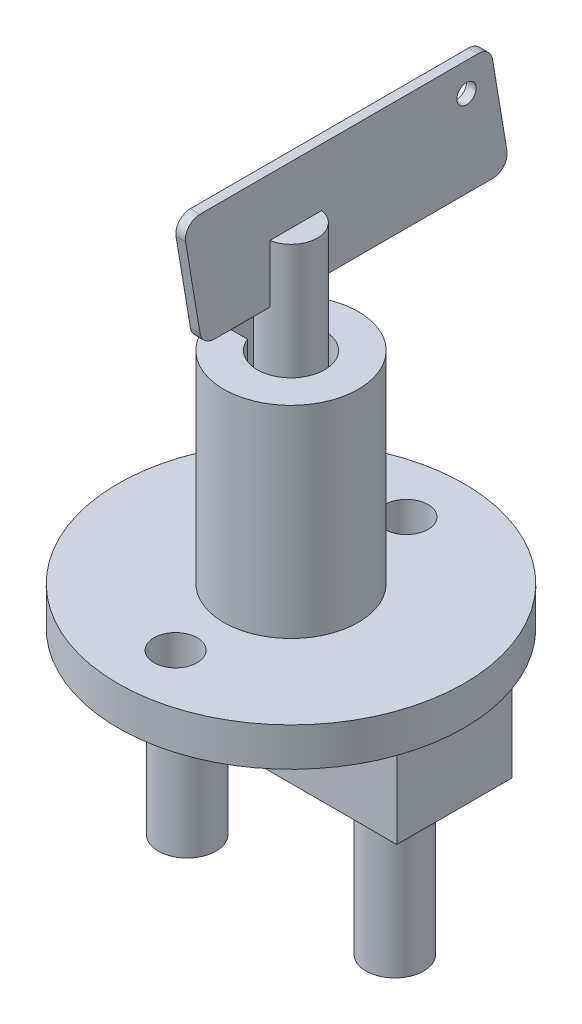
SolidWorks part; units mm, degrees
material "ABS"
ref_plane "Plane1" through (0, 0, 0) normal (0, 0, 1) x (1, 0, 0)
ref_plane "Plane2" through (0, 0, 0) normal (0, 1, 0) x (1, 0, 0)
ref_plane "Plane3" through (0, 0, 0) normal (1, 0, 0) x (0, 0, -1)
sketch "Sketch1" plane through (0, 0, 0) normal (0, 1, 0) x (1, 0, 0)
  line L0 (0, 19.05) -> (0, -19.05) construction
  circle A0 centre (0, 0) radius 28.575
  circle A1 centre (0, 19.05) radius 3.5719
  circle A2 centre (0, -19.05) radius 3.5719
  dimension "D1" = 57.15
  dimension "D2" = 7.1437
  dimension "D3" = 38.1
extrude "Extrude1" add sketch "Sketch1" along normal blind 6.35
sketch "Sketch2" plane through (0, 6.35, 0) normal (0, 1, 0) x (-1, 0, 0)
  circle A0 centre (0, 0) radius 11.1125
  dimension "D1" = 22.225
extrude "Extrude2" add sketch "Sketch2" along normal blind 33.3375
sketch "Sketch3" plane through (0, 39.6875, 0) normal (0, 1, 0) x (-1, 0, 0)
  line L0 (7.9375, 0) -> (0, 0) construction
  line L1 (7.9375, -1.9844) -> (5.1898, -1.9844)
  line L2 (7.9375, -1.9844) -> (7.9375, 1.9844)
  line L3 (7.9375, 1.9844) -> (5.1898, 1.9844)
  arc A0 (5.1898, 1.9844) -> (5.1898, -1.9844) centre (0, 0) ccw
  dimension "D1" = 11.1125
  dimension "D2" = 3.9688
  dimension "D3" = 7.9375
extrude "Cut-Extrude1" cut sketch "Sketch3" against normal blind 25.4
sketch "Sketch4" plane through (0, 0, 0) normal (0, -1, 0) x (1, 0, 0)
  line L0 (-26.9875, -9.525) -> (26.9875, 9.525) construction
  line L1 (-26.9875, -9.525) -> (26.9875, -9.525)
  line L2 (-26.9875, -9.525) -> (-26.9875, 9.525)
  line L3 (-26.9875, 9.525) -> (26.9875, 9.525)
  line L4 (26.9875, -9.525) -> (26.9875, 9.525)
  point P4 (0, 0)
  dimension "D1" = 53.975
  dimension "D2" = 19.05
extrude "Extrude3" add sketch "Sketch4" along normal blind 12.7
sketch "Sketch5" plane through (0, -12.7, 0) normal (0, -1, 0) x (1, 0, 0)
  line L0 (-17.145, 0) -> (0, 0) construction
  circle A0 centre (-17.145, 0) radius 4.7625
  dimension "D1" = 9.525
  dimension "D2" = 17.145
extrude "Extrude4" add sketch "Sketch5" along normal blind 25.4
mirror "Mirror1" about plane through (0, 0, 0) normal (1, 0, 0) of "Extrude4"
sketch "Sketch6" plane through (0, 39.6875, 0) normal (0, 1, 0) x (-1, 0, 0)
  circle A0 centre (0, 0) radius 4.3656
  dimension "D1" = 8.7312
extrude "Extrude5" add sketch "Sketch6" along normal mid plane 36.5125 separate body
sketch "Sketch7" plane through (0, 0, 0) normal (1, 0, 0) x (0, 0, -1)
  line L0 (-15.4781, 48.4187) -> (-18.6531, 67.4688)
  line L1 (-18.6531, 67.4688) -> (32.1469, 67.4688)
  line L2 (32.1469, 67.4688) -> (35.3219, 48.4188)
  line L3 (-4.3656, 21.4313) -> (4.3656, 21.4313) construction
  line L4 (-15.4781, 48.4187) -> (35.3219, 48.4188)
  line L5 (-4.3656, 57.9438) -> (-4.3656, 21.4312) construction
  dimension "D1" = 50.8
  dimension "D2" = 19.05
  dimension "D3" = 3.175
  dimension "D4" = 26.9875
  dimension "D5" = 11.1125
extrude "Extrude6" add sketch "Sketch7" along normal mid plane 1.5875
fillet "Fillet1" radius 2.3813 4 edges at (0, 48.4188, -35.3219) (0, 67.4688, -32.1469) (0, 48.4187, 15.4781) (0, 67.4688, 18.6531)
sketch "Sketch8" plane through (0.7937, 0, 0) normal (1, 0, 0) x (0, 0, -1)
  line L0 (4.3656, 21.4312) -> (4.3656, 48.4187) construction
  line L1 (30.1297, 67.4688) -> (-15.8422, 67.4688) construction
  circle A0 centre (28.1781, 62.7062) radius 1.5875
  dimension "D1" = 3.175
  dimension "D2" = 23.8125
  dimension "D3" = 4.7625
extrude "Cut-Extrude2" cut sketch "Sketch8" against normal up to next (1.5875 mm away)
sketch "Sketch9" plane through (0, 0, 0) normal (0, 0, 1) x (1, 0, 0)
  line L0 (-4.3656, 21.4313) -> (4.3656, 21.4313) construction
  line L1 (0, 27.7812) -> (0, 0) construction
  circle A0 centre (0, 27.7812) radius 1.9844
  dimension "D1" = 3.9688
  dimension "D2" = 6.35
extrude "Extrude7" add sketch "Sketch9" against normal blind 6.35
